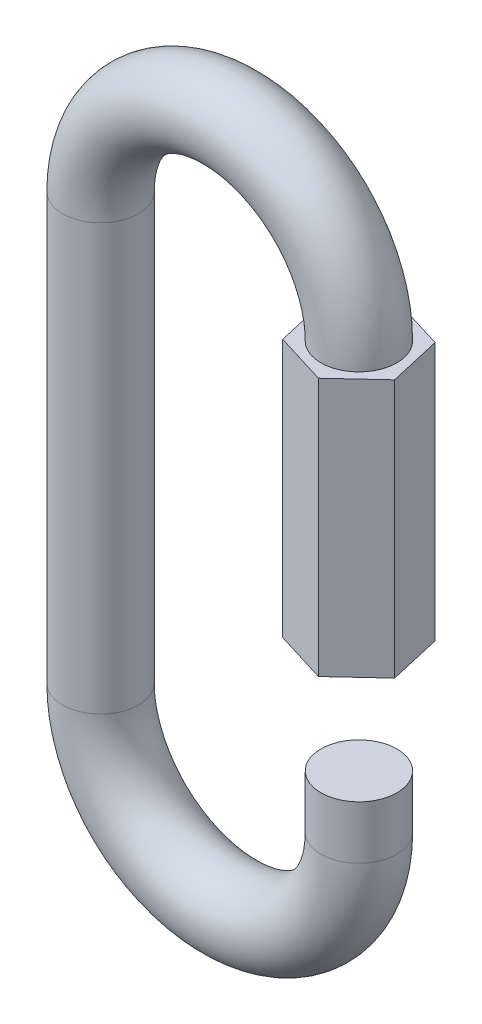
SolidWorks part; units mm, degrees
material "AISI 1020"
ref_plane "Front Plane" through (0, 0, 0) normal (0, 0, 1) x (1, 0, 0)
ref_plane "Top Plane" through (0, 0, 0) normal (0, 1, 0) x (1, 0, 0)
ref_plane "Right Plane" through (0, 0, 0) normal (1, 0, 0) x (0, 0, -1)
sketch "Sketch1" plane through (0, 0, 0) normal (0, 1, 0) x (1, 0, 0)
  circle A0 centre (0, 0) radius 2.5
  dimension "D1" = 5
sketch "Sketch2" plane through (0, 0, 0) normal (0, 0, 1) x (1, 0, 0)
  line L0 (0, 0) -> (0, 17)
  line L1 (2.5, 0) -> (-2.5, 0) construction
  line L2 (-17, 17) -> (-17, -11)
  line L3 (0, -11) -> (0, -7.5)
  arc A0 (0, 17) -> (-17, 17) centre (-8.5, 17) ccw
  arc A1 (-17, -11) -> (0, -11) centre (-8.5, -11) ccw
  point P9 (-8.5, 25.5)
  point P12 (-8.5, -19.5)
  point P13 (0, 0)
  point P14 (-3.5, -21)
  point P15 (0, 17)
  dimension "D1" = 45
  dimension "D2" = 17
  dimension "D3" = 7.5
  dimension "D4" = 17
sweep "Sweep1" add profiles "Sketch1" path "Sketch2"
sketch "Sketch3" plane through (0, 0, 0) normal (0, -1, 0) x (1, 0, 0)
  line L1 (3.3909, 1.0436) -> (0.7917, 3.4584)
  line L2 (0.7917, 3.4584) -> (-2.5992, 2.4148)
  line L3 (-2.5992, 2.4148) -> (-3.3909, -1.0436)
  line L4 (-3.3909, -1.0436) -> (-0.7917, -3.4584)
  line L5 (-0.7917, -3.4584) -> (2.5992, -2.4148)
  line L6 (2.5992, -2.4148) -> (3.3909, 1.0436)
  circle A0 centre (0, 0) radius 3.0726 construction
extrude "Boss-Extrude1" add sketch "Sketch3" against normal blind 17
